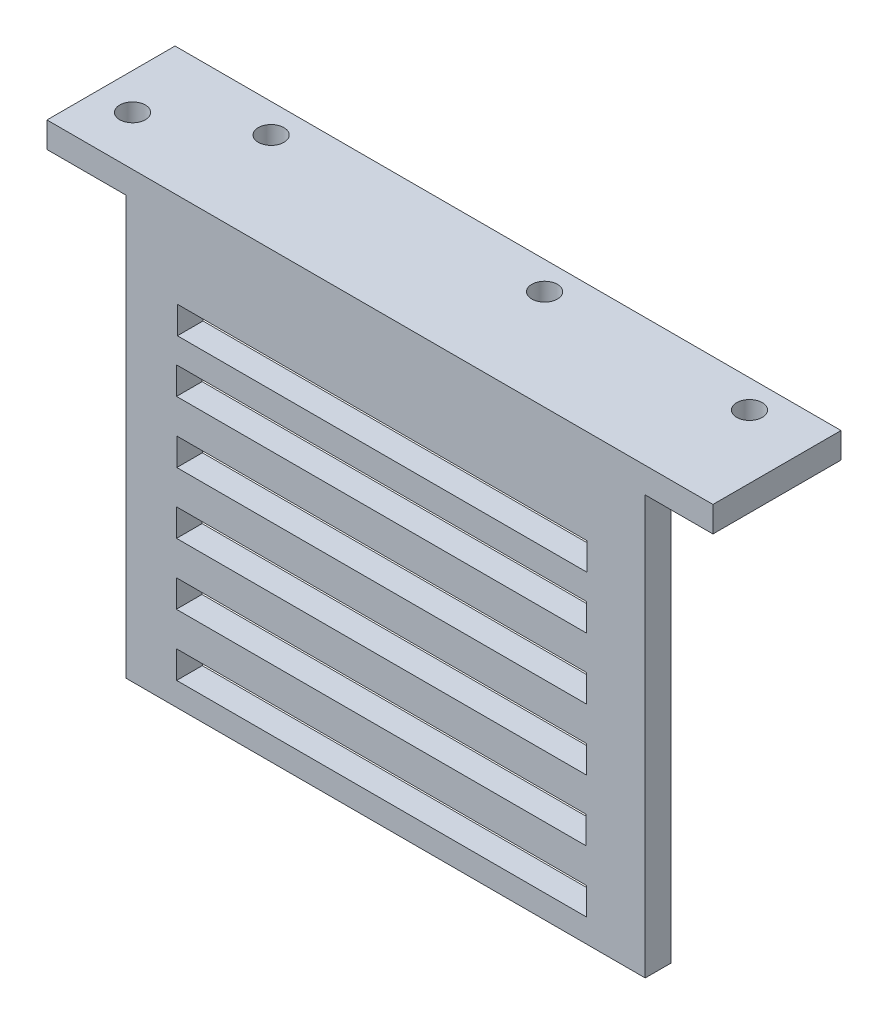
SolidWorks part; units mm, degrees
ref_plane "前视基准面" through (0, 0, 0) normal (0, 0, 1) x (1, 0, 0)
ref_plane "上视基准面" through (0, 0, 0) normal (0, 1, 0) x (1, 0, 0)
ref_plane "右视基准面" through (0, 0, 0) normal (1, 0, 0) x (0, 0, -1)
other "Configuration Table"
sketch "草图1" plane through (0, 0, 0) normal (0, 1, 0) x (1, 0, 0)
  line L1 (-39, -7.5) -> (39, -7.5)
  line L2 (-39, -7.5) -> (-39, 7.5)
  line L3 (-39, 7.5) -> (39, 7.5)
  line L4 (39, -7.5) -> (39, 7.5)
  line L5 (-39, -7.5) -> (39, 7.5) construction
  line L6 (-39, 7.5) -> (39, -7.5) construction
  point P0 (0, 0)
  dimension "D1" = 15
  dimension "D2" = 78
extrude "凸台-拉伸1" add sketch "草图1" along normal blind 3 contours L2 L1 L4 L3
sketch "草图3" plane through (0, 3, 0) normal (0, 1, 0) x (1, 0, 0)
  line L0 (-39, -7.5) -> (-39, 7.5) construction
  line L1 (-39, 7.5) -> (39, 7.5) construction
  circle A0 centre (-34.76, -1.72) radius 1.5
  circle A1 centre (-24.35, 4.1) radius 1.5
  circle A2 centre (31.56, 4.2217) radius 1.5
  circle A3 centre (7.56, 4.2217) radius 1.5
  point P2 (0, 0)
  point P11 (27.5737, 4.2217)
  point P12 (6.7297, 4.2217)
  point P13 (-31.0334, 4.2217)
  point P14 (-26.0415, 4.2217)
  point P17 (-24.5173, 0.3349)
  dimension "D1" = 4.24
  dimension "D2" = 10.41
  dimension "D3" = 3.4
  dimension "D4" = 5.82
  dimension "D5" = 31.91
  dimension "D6" = 24
extrude "切除-拉伸1" cut sketch "草图3" against normal blind 3
sketch "草图4" plane through (0, 3, 0) normal (0, 1, 0) x (1, 0, 0)
  line L0 (-39, -7.5) -> (-39, 7.5) construction
  circle A0 centre (-3, -1.2342) radius 6
  point P4 (-3, -1.2342)
  dimension "D1" = 36
extrude "凸台-拉伸2" add sketch "草图4" along normal blind 18
sketch "草图5" plane through (0, 21, 0) normal (0, 1, 0) x (1, 0, 0)
  circle A0 centre (-3, -1.2342) radius 4.5
extrude "切除-拉伸2" cut sketch "草图5" against normal blind 21
hole_wizard "Ø2.0mm 暗销孔2" positions "3D草图5" profile "草图8" hole size "Ø2.0" standard "ANSI Metric"
sketch3d "3D草图5"
  point P0 (-7.9013, 17.3421, 4.6949)
  point P2 (1.0718, 17.1648, 5.6411)
sketch "草图8" plane through (-7.9013, 17.3421, 4.6949) normal (0, 1, 0) x (0.5768, 0, 0.8169)
  line L0 (0, 0) -> (0, 6)
  line L1 (0, 6) -> (1.5, 4.5)
  line L2 (1.5, 4.5) -> (1.5, 0)
  line L5 (1.5, 0) -> (0, 0)
  line L10 (0, 6) -> (-1.5, 4.5) construction
  line L11 (0, -6.35) -> (0, 107.95) construction
  dimension "孔直径" = 3
  dimension "孔深度" = 6
  dimension "导头角度" = 90
sketch "草图10" plane through (0, 0, -7.5) normal (0, 0, -1) x (-1, 0, 0)
  line L0 (39, 3) -> (-39, 3) construction
  line L1 (0, 3) -> (6, 3)
  line L2 (0, 3) -> (0, 13)
  line L3 (0, 13) -> (6, 13)
  line L4 (6, 3) -> (6, 13)
  point P6 (6.8148, 13.7899)
  point P7 (6.7809, 13.0053)
  point P8 (0, 0)
  point P9 (7.0332, 12.5658)
  dimension "D1" = 6
  dimension "D2" = 10
extrude "切除-拉伸3" cut sketch "草图10" against normal blind 7
sketch "草图13" plane through (0, 0, -7.5) normal (0, 0, -1) x (-1, 0, 0)
  line L0 (39, 3) -> (-39, 3) construction
  line L1 (-6.6034, 3) -> (13.2323, 3)
  line L2 (-6.6034, 3) -> (-6.6034, 24.6102)
  line L3 (-6.6034, 24.6102) -> (13.2323, 24.6102)
  line L4 (13.2323, 3) -> (13.2323, 24.6102)
extrude "切除-拉伸4" cut sketch "草图13" against normal blind 20
sketch "草图14" plane through (0, 3, 0) normal (0, 1, 0) x (1, 0, 0)
  line L1 (-8.751, 3.9817) -> (2.7721, 3.9817)
  line L2 (-8.751, 3.9817) -> (-8.751, -6.5086)
  line L3 (-8.751, -6.5086) -> (2.7721, -6.5086)
  line L4 (2.7721, 3.9817) -> (2.7721, -6.5086)
extrude "凸台-拉伸3" add sketch "草图14" against normal blind 3
sketch "草图18" plane through (0, 0, 0) normal (0, -1, 0) x (1, 0, 0)
  line L1 (-39, 7.5) -> (39, 7.5)
  line L2 (-39, 7.5) -> (-39, 15.5)
  line L3 (-39, 15.5) -> (39, 15.5)
  line L4 (39, 7.5) -> (39, 15.5)
  dimension "D1" = 8
extrude "凸台-拉伸4" add sketch "草图18" against normal blind 3
sketch "草图19" plane through (0, 0, 0) normal (0, -1, 0) x (1, 0, 0)
  line L0 (39, 15.5) -> (-39, 15.5) construction
  line L1 (-17.5447, 15.5) -> (19.2232, 15.5)
  line L2 (-17.5447, 15.5) -> (-17.5447, 13)
  line L3 (-17.5447, 13) -> (19.2232, 13)
  line L4 (19.2232, 15.5) -> (19.2232, 13)
  dimension "D1" = 2.5
extrude "凸台-拉伸5" add sketch "草图19" along normal blind 12.5
sketch "草图20" plane through (0, 0, 13) normal (0, 0, -1) x (-1, 0, 0)
  circle A0 centre (-6.7687, -6.2144) radius 1.65
  circle A1 centre (6.2313, -6.2144) radius 1.65
  point P4 (0, 0)
  point P5 (0, 0)
  point P6 (1.0873, -6.2144)
  dimension "D1" = 13
sketch "草图23" plane through (0, 0, 13) normal (0, 0, -1) x (-1, 0, 0)
  line L0 (-19.2232, -12.5) -> (-19.2232, 0) construction
  circle A4 centre (-8.6032, -6.0559) radius 1.65
  circle A5 centre (2.5968, -6.0559) radius 1.65
  dimension "D1" = 10.62
  dimension "D2" = 11.2
extrude "切除-拉伸6" cut sketch "草图23" against normal blind 12.5
sketch "草图24" plane through (0, 0, 13) normal (0, 0, -1) x (-1, 0, 0)
  circle A0 centre (-8.6032, -6.0559) radius 1.65 construction
  circle A1 centre (-8.6032, -6.0559) radius 1.65
  circle A2 centre (2.5968, -6.0559) radius 1.65 construction
  circle A3 centre (2.5968, -6.0559) radius 1.65
  circle A4 centre (4.1968, -6.0559) radius 1.6
  dimension "D2" = 12.8
  dimension "D1" = 11.2
sketch "草图25" plane through (0, 0, 13) normal (0, 0, -1) x (-1, 0, 0)
  line L1 (0.2124, -3.7444) -> (4.449, -3.7444)
  line L2 (0.2124, -3.7444) -> (0.2124, -9.1085)
  line L3 (0.2124, -9.1085) -> (4.449, -9.1085)
  line L4 (4.449, -3.7444) -> (4.449, -9.1085)
extrude "凸台-拉伸7" add sketch "草图25" against normal blind 2.5
sketch "草图26" plane through (0, 0, 13) normal (0, 0, -1) x (-1, 0, 0)
  circle A0 centre (4.1968, -6.0559) radius 1.6 construction
  circle A1 centre (4.1968, -6.0559) radius 1.6
extrude "切除-拉伸7" cut sketch "草图26" against normal blind 2.5
sketch "草图27" plane through (0, 0, 13) normal (0, 0, -1) x (-1, 0, 0)
  line L1 (-13.0523, -3.3946) -> (8.2937, -3.3946)
  line L2 (-13.0523, -3.3946) -> (-13.0523, -9.9889)
  line L3 (-13.0523, -9.9889) -> (8.2937, -9.9889)
  line L4 (8.2937, -3.3946) -> (8.2937, -9.9889)
extrude "凸台-拉伸8" add sketch "草图27" against normal blind 2.5
sketch "草图28" plane through (0, 0, 13) normal (0, 0, -1) x (-1, 0, 0)
  line L1 (-19.2232, -12.5) -> (17.544, -12.5)
  line L2 (-19.2232, -12.5) -> (-19.2232, -18.4182)
  line L3 (-19.2232, -18.4182) -> (17.544, -18.4182)
  line L4 (17.544, -12.5) -> (17.544, -18.4182)
extrude "凸台-拉伸9" add sketch "草图28" against normal blind 2.5
sketch "草图29" plane through (0, 0, 13) normal (0, 0, -1) x (-1, 0, 0)
  line L1 (-14.4639, -11.6442) -> (13.1964, -11.6442)
  line L2 (-14.4639, -11.6442) -> (-14.4639, -15.1442)
  line L3 (-14.4639, -15.1442) -> (13.1964, -15.1442)
  line L4 (13.1964, -11.6442) -> (13.1964, -15.1442)
  dimension "D1" = 3.5
extrude "切除-拉伸9" cut sketch "草图29" against normal blind 2.5
sketch "草图30" plane through (0, 3, 0) normal (0, 1, 0) x (1, 0, 0)
  line L0 (39, -15.5) -> (39, 7.5) construction
  line L1 (-39, -15.5) -> (39, -15.5)
  line L2 (-39, -15.5) -> (-39, -7.5)
  line L3 (-39, -7.5) -> (39, -7.5)
  line L4 (39, -15.5) -> (39, -7.5)
  line L5 (-39, 7.5) -> (39, 7.5) construction
  dimension "D1" = 15
extrude "切除-拉伸10" cut sketch "草图30" against normal blind 100
sketch "草图31" plane through (0, 0, 0) normal (0, -1, 0) x (1, 0, 0)
  line L0 (39, 7.5) -> (-39, 7.5) construction
  line L1 (-29.754, 7.5) -> (31.0662, 7.5)
  line L2 (-29.754, 7.5) -> (-29.754, 4.5)
  line L3 (-29.754, 4.5) -> (31.0662, 4.5)
  line L4 (31.0662, 7.5) -> (31.0662, 4.5)
  dimension "D1" = 3
extrude "凸台-拉伸10" add sketch "草图31" along normal blind 49
sketch "草图32" plane through (0, 0, 4.5) normal (0, 0, -1) x (-1, 0, 0)
  line L0 (-24.1534, -35.8541) -> (23.8466, -35.8541)
  line L1 (-24.1893, -43.0541) -> (23.8107, -43.0541)
  line L2 (-24.1893, -43.0541) -> (-24.1893, -46.2541)
  line L3 (-24.1893, -46.2541) -> (23.8107, -46.2541)
  line L4 (23.8107, -43.0541) -> (23.8107, -46.2541)
  line L5 (-24.1534, -35.8541) -> (-24.1534, -39.0541)
  line L6 (-24.1534, -39.0541) -> (23.8466, -39.0541)
  line L7 (23.8466, -35.8541) -> (23.8466, -39.0541)
  line L8 (-24.1733, -28.6541) -> (23.8267, -28.6541)
  line L9 (-24.1733, -28.6541) -> (-24.1733, -31.8541)
  line L10 (-24.1733, -31.8541) -> (23.8267, -31.8541)
  line L11 (23.8267, -28.6541) -> (23.8267, -31.8541)
  line L12 (-24.2052, -21.4541) -> (23.7948, -21.4541)
  line L13 (-24.2052, -21.4541) -> (-24.2052, -24.6541)
  line L14 (-24.2052, -24.6541) -> (23.7948, -24.6541)
  line L15 (23.7948, -21.4541) -> (23.7948, -24.6541)
  line L16 (-24.1756, -14.2541) -> (23.8244, -14.2541)
  line L17 (-24.1756, -14.2541) -> (-24.1756, -17.4541)
  line L18 (-24.1756, -17.4541) -> (23.8244, -17.4541)
  line L19 (23.8244, -14.2541) -> (23.8244, -17.4541)
  line L20 (-24.2763, -8.0541) -> (23.7237, -8.0541)
  line L21 (-24.2763, -8.0541) -> (-24.2763, -11.2541)
  line L22 (-24.2763, -11.2541) -> (23.7237, -11.2541)
  line L23 (23.7237, -8.0541) -> (23.7237, -11.2541)
  dimension "D1" = 3.2
  dimension "D2" = 48
  dimension "D3" = 4
  dimension "D4" = 4
  dimension "D5" = 4
  dimension "D6" = 4
  dimension "D7" = 3
extrude "切除-拉伸11" cut sketch "草图32" against normal blind 49 contours L19 L16 L17 L18 | L15 L12 L13 L14 | L11 L8 L9 L10 | L7 L0 L5 L6 | L4 L1 L2 L3 | L20 L23 L22 L21
